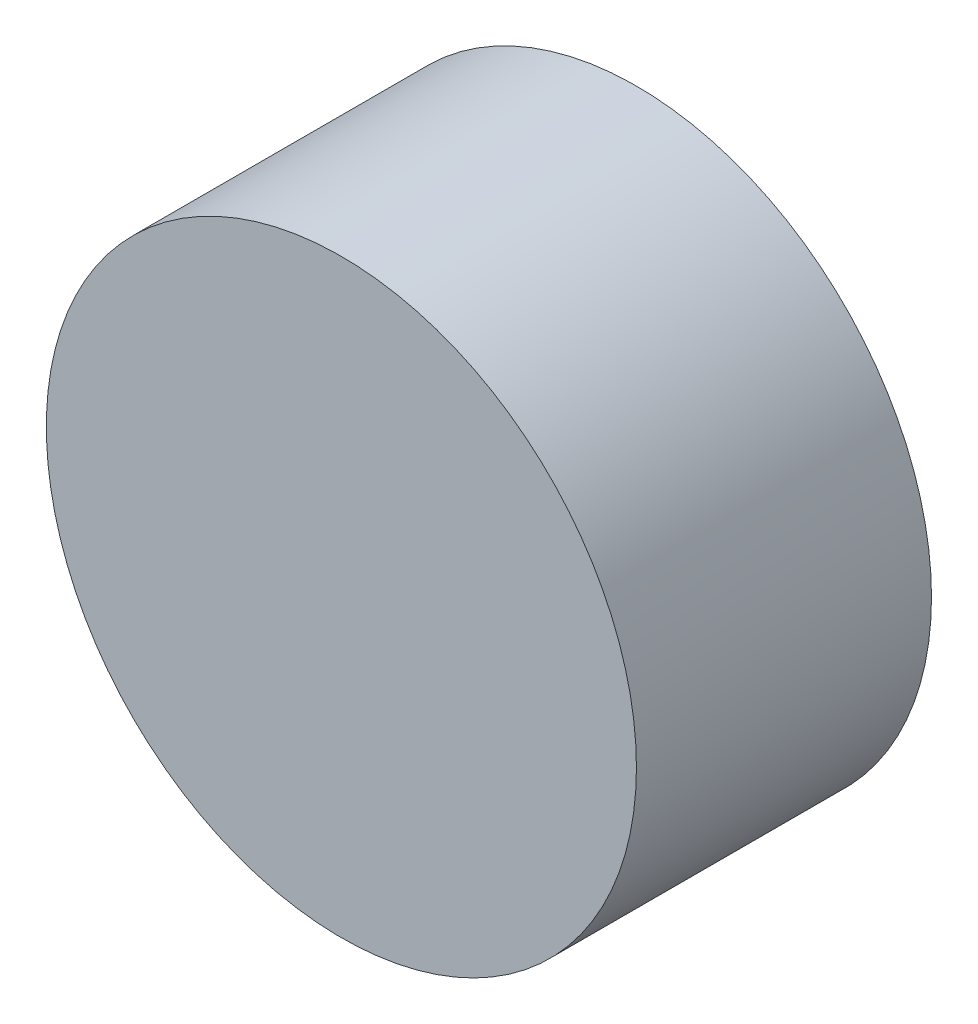
SolidWorks part; units mm, degrees
material "1.4105 (X6CrMoS17)"
ref_plane "Přední rovina" through (0, 0, 0) normal (0, 0, 1) x (1, 0, 0)
ref_plane "Horní rovina" through (0, 0, 0) normal (0, 1, 0) x (1, 0, 0)
ref_plane "Pravá rovina" through (0, 0, 0) normal (1, 0, 0) x (0, 0, -1)
sketch "Skica1" plane through (0, 0, 0) normal (0, 0, 1) x (1, 0, 0)
  circle A0 centre (0, 0) radius 5
  dimension "D1" = 10
extrude "Přidat vysunutím1" add sketch "Skica1" along normal blind 5
